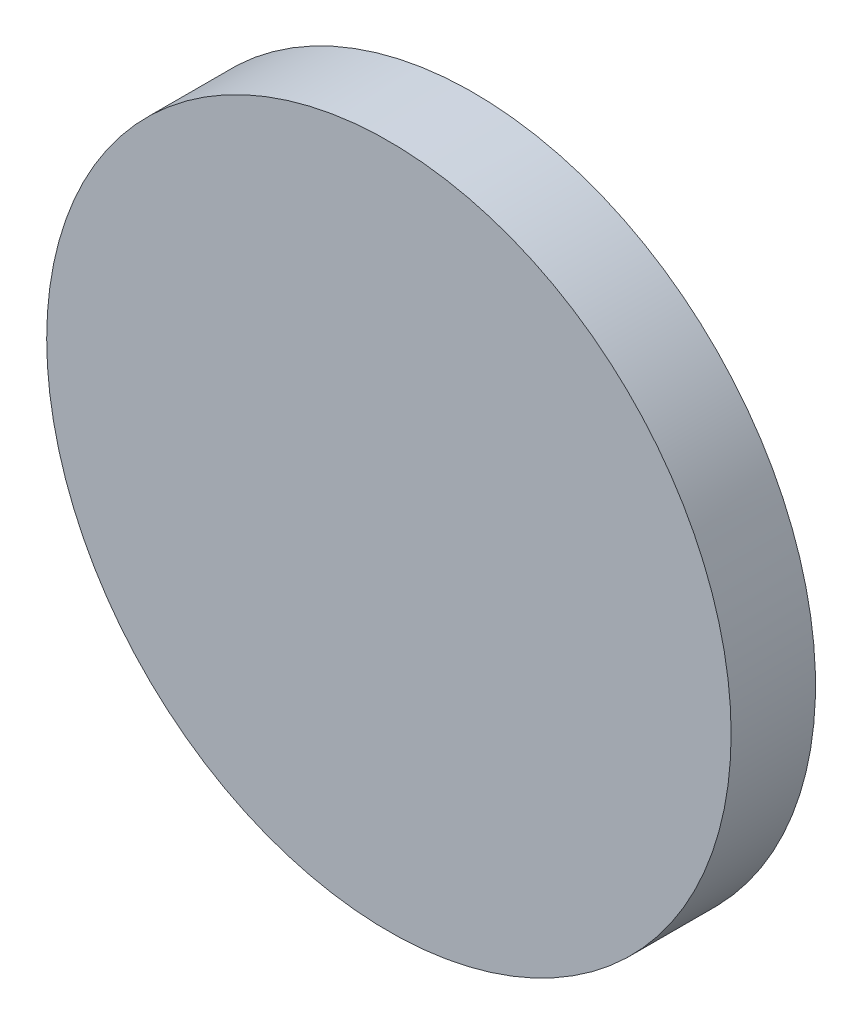
SolidWorks part; units mm, degrees
ref_plane "前视基准面" through (0, 0, 0) normal (0, 0, 1) x (1, 0, 0)
ref_plane "上视基准面" through (0, 0, 0) normal (0, 1, 0) x (1, 0, 0)
ref_plane "右视基准面" through (0, 0, 0) normal (1, 0, 0) x (0, 0, -1)
sketch "草图1" plane through (0, 0, 0) normal (0, 0, 1) x (1, 0, 0)
  circle A0 centre (0, 0) radius 23.5
  circle A1 centre (0, 0) radius 25.5
  dimension "D1" = 47
  dimension "D2" = 2
extrude "凸台-拉伸2" add sketch "草图1" along normal blind 15
sketch "草图3" plane through (0, 0, 0) normal (0, 0, 1) x (1, 0, 0)
  circle A0 centre (0, 0) radius 29.5
  circle A1 centre (0, 0) radius 36.5
  dimension "D1" = 59
  dimension "D2" = 7
extrude "凸台-拉伸3" add sketch "草图3" along normal blind 15 separate body
sketch "草图5" plane through (0, 0, 0) normal (0, 1, 0) x (1, 0, 0)
  line L0 (-29.5, 0) -> (-29.5, -15) construction
  line L1 (-29.5, -15) -> (29.5, -15) construction
  line L2 (-29.5, -3) -> (-29.5, -13)
  line L3 (0, 0) -> (0, -20.0684) construction
  arc A0 (-29.5, -3) -> (-29.5, -13) centre (-29.5, -8) ccw
  point P6 (-29.5, -3)
  dimension "D1" = 10
  dimension "D2" = 7
revolve "切除-旋转2" cut sketch "草图5" angle 360 about L3
sketch "草图6" plane through (0, 0, 0) normal (0, 0, -1) x (-1, 0, 0)
  circle A1 centre (0, 0) radius 47.8523
extrude "切除-拉伸1" cut sketch "草图6" against normal blind 8
sketch "草图9" plane through (0, 0, 15) normal (0, 0, 1) x (1, 0, 0)
  circle A0 centre (0, 0) radius 36.5
extrude "凸台-拉伸5" add sketch "草图9" along normal blind 2
